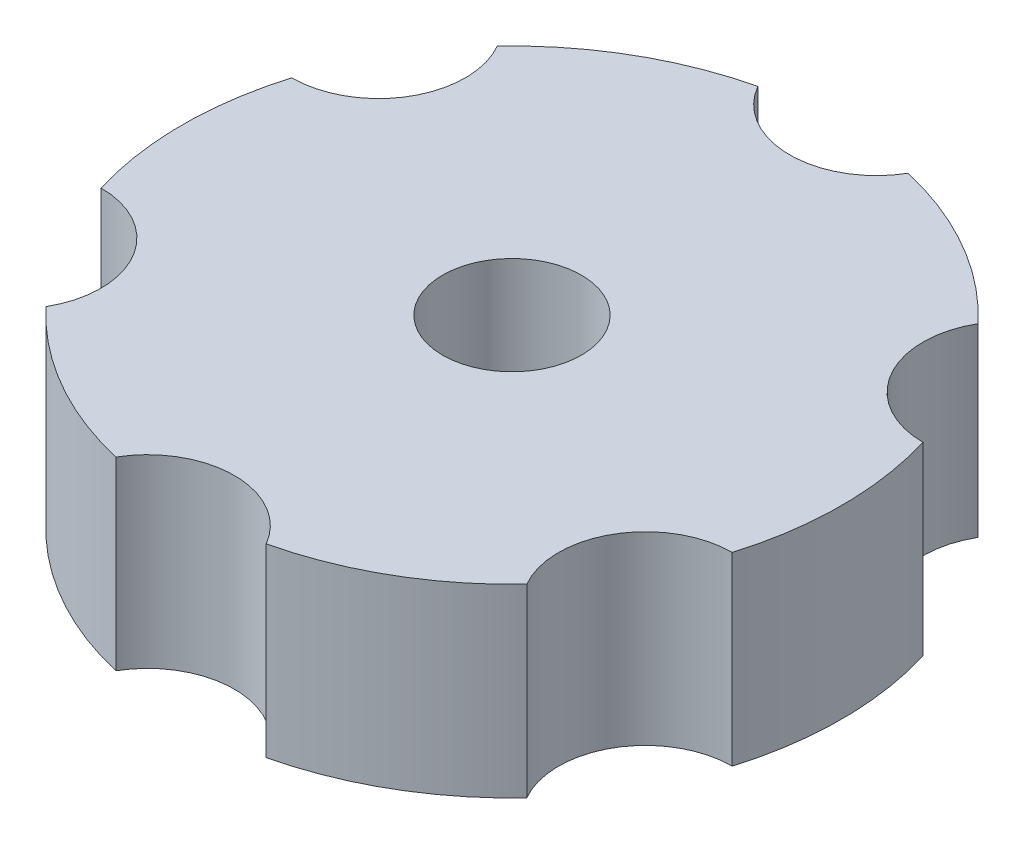
SolidWorks part; units mm, degrees
ref_plane "Alzado" through (0, 0, 0) normal (0, 0, 1) x (1, 0, 0)
ref_plane "Planta" through (0, 0, 0) normal (0, 1, 0) x (1, 0, 0)
ref_plane "Vista lateral" through (0, 0, 0) normal (1, 0, 0) x (0, 0, -1)
sketch "Croquis1" plane through (0, 0, 0) normal (0, 1, 0) x (1, 0, 0)
  line L0 (0, 0) -> (0, 31.5095) construction
  line L1 (-6.5, 27.7489) -> (6.5, 27.7489) construction
  line L2 (0, 24) -> (15.3704, 24) construction
  circle A0 centre (0, 0) radius 28.5
  circle A1 centre (0, 31.5095) radius 7.5095
  circle A2 centre (27.288, 15.7547) radius 7.5095
  circle A3 centre (27.288, -15.7547) radius 7.5095
  circle A4 centre (0, -31.5095) radius 7.5095
  circle A5 centre (-27.288, -15.7547) radius 7.5095
  circle A6 centre (-27.288, 15.7547) radius 7.5095
  circle A7 centre (0, 0) radius 6
  point P22 (0, 0)
  dimension "D1" = 57
  dimension "D5" = 12
  dimension "D2" = 13
  dimension "D3" = 24
  dimension "D4" = 6
extrude "Saliente-Extruir1" add sketch "Croquis1" along normal blind 16 contours A6 A0 A5 A4 A3 A2 A1 A7
